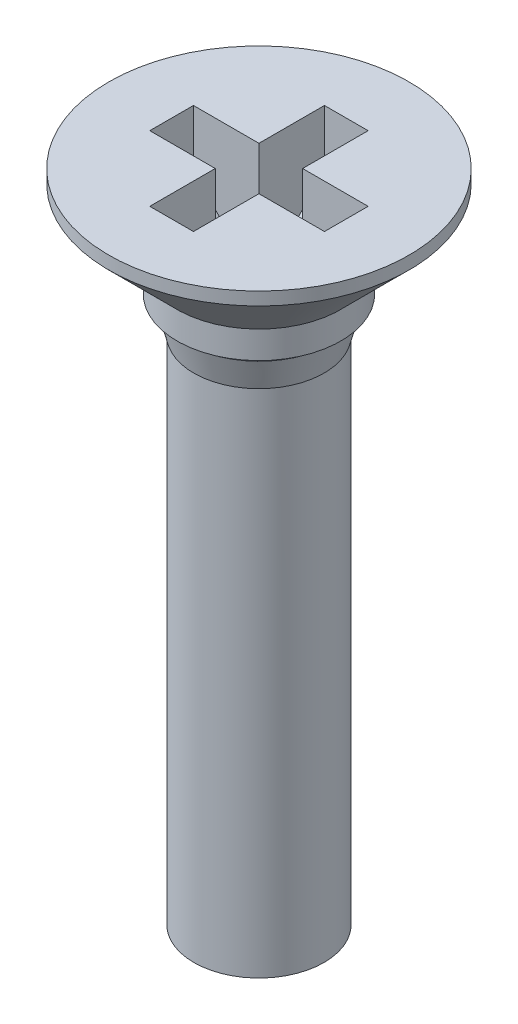
SolidWorks part; units mm, degrees
ref_plane "Vorderseite" through (0, 0, 0) normal (0, 0, 1) x (1, 0, 0)
ref_plane "Oben" through (0, 0, 0) normal (0, 1, 0) x (1, 0, 0)
ref_plane "Rechts" through (0, 0, 0) normal (1, 0, 0) x (0, 0, -1)
sketch "Skizze1" plane through (0, 0, 0) normal (0, 0, 1) x (1, 0, 0)
  line L0 (0, 0) -> (2.75, 0)
  line L1 (2.75, 0) -> (2.75, -0.2375)
  line L2 (2.75, -0.2375) -> (1.5, -1.4875)
  line L3 (1.3375, -1.9875) -> (1.3375, -2.1126)
  line L4 (1.3375, -2.1126) -> (1.1935, -2.65)
  line L5 (1.1935, -2.65) -> (1.1935, -8)
  line L6 (1.1935, -8) -> (0, -8)
  line L7 (0, 0) -> (0, -8) construction
  line L8 (0, 0) -> (0, -8)
  line L10 (1.5, -1.4875) -> (1.5, -1.9875)
  line L12 (1.5, -1.9875) -> (1.3375, -1.9875)
  point P3 (1.3375, -1.65)
  dimension "D1" = 45
  dimension "D2" = 15
  dimension "K" = 1.65
  dimension "DA" = 5.5
  dimension "DK" = 2.387
  dimension "L" = 8
  dimension "DG" = 3
  dimension "A" = 1
  dimension "DF" = 2.675
  dimension "P" = 0.5
revolve "Basis-Rotation" add sketch "Skizze1" angle 360 about L7
sketch "Skizze2" plane through (0, 0, 0) normal (0, 0, 1) x (1, 0, 0)
  line L0 (0, -2.1) -> (0, 0) construction
  line L1 (0, 0) -> (0, -8) construction
  line L2 (-0.55, -2.1) -> (0.55, -2.1)
  line L3 (1.6, 0) -> (1.6, -1.05)
  line L4 (1.6, -1.05) -> (0.55, -2.1)
  line L5 (1.6, 0) -> (-1.6, 0)
  line L6 (-1.6, -1.05) -> (-0.55, -2.1)
  line L7 (-1.6, 0) -> (-1.6, -1.05)
  line L8 (0, -1.05) -> (1.6, -1.05) construction
  line L9 (2.75, 0) -> (-2.75, 0) construction
  line L11 (1.5, -1.4875) -> (2.75, -0.2375) construction
  point P11 (0, 0)
  dimension "M" = 3.2
  dimension "T" = 2.1
extrude "Kreuzschlitz1 H" cut sketch "Skizze2" against normal blind 0.4 and the other way blind 0.4
sketch "Skizze3" plane through (0, 0, 0) normal (1, 0, 0) x (0, 0, -1)
  line L0 (0, -2.1) -> (0, 0) construction
  line L2 (-0.55, -2.1) -> (0.55, -2.1)
  line L3 (1.6, 0) -> (1.6, -1.05)
  line L4 (1.6, -1.05) -> (0.55, -2.1)
  line L5 (1.6, 0) -> (-1.6, 0)
  line L6 (-1.6, -1.05) -> (-0.55, -2.1)
  line L7 (-1.6, 0) -> (-1.6, -1.05)
  line L8 (0, -1.05) -> (1.6, -1.05) construction
  point P11 (0, 0)
extrude "Kreuzschlitz2 H" cut sketch "Skizze3" against normal blind 0.4 and the other way blind 0.4
sketch "Skizze4" plane through (2.4522, 0, -1.8507) normal (0, 1, 0) x (-1, 0, 0)
  line L0 (7.3522, 1.8507) -> (-2.4478, 1.8507) construction
  line L1 (2.4522, -3.0493) -> (2.4522, 6.7507) construction
  line L2 (-2.4478, 1.0342) -> (-2.4478, 2.6672)
  line L3 (-2.4478, 1.0342) -> (0.0059, 1.0342)
  line L4 (0.0059, 1.0342) -> (0.8191, 0.6258)
  line L5 (1.2273, 0.2176) -> (-1.0126, -1.6141)
  line L6 (0.8191, 0.6258) -> (-1.0126, -1.6141)
  line L7 (1.6357, -0.5956) -> (1.2273, 0.2176)
  line L8 (1.6357, -3.0493) -> (1.6357, -0.5956)
  line L9 (1.6357, -3.0493) -> (3.2687, -3.0493)
  line L10 (3.2687, -3.0493) -> (3.2687, -0.5956)
  line L11 (3.2687, -0.5956) -> (3.6772, 0.2176)
  line L12 (2.4522, 1.8507) -> (-1.0126, -1.6141) construction
  line L13 (4.0854, 0.6258) -> (5.917, -1.6141)
  line L14 (3.6772, 0.2176) -> (5.917, -1.6141)
  line L15 (4.8986, 1.0342) -> (4.0854, 0.6258)
  line L16 (7.3522, 1.0342) -> (4.8986, 1.0342)
  line L17 (7.3522, 1.0342) -> (7.3522, 2.6672)
  line L18 (7.3522, 2.6672) -> (4.8986, 2.6672)
  line L19 (4.8986, 2.6672) -> (4.0854, 3.0757)
  line L20 (3.6772, 3.4839) -> (5.917, 5.3156)
  line L21 (4.0854, 3.0757) -> (5.917, 5.3156)
  line L22 (3.2687, 4.2971) -> (3.6772, 3.4839)
  line L23 (3.2687, 6.7507) -> (3.2687, 4.2971)
  line L24 (1.6357, 6.7507) -> (3.2687, 6.7507)
  line L25 (1.6357, 6.7507) -> (1.6357, 4.2971)
  line L26 (1.6357, 4.2971) -> (1.2273, 3.4839)
  line L27 (0.8191, 3.0757) -> (-1.0126, 5.3156)
  line L28 (1.2273, 3.4839) -> (-1.0126, 5.3156)
  line L29 (0.0059, 2.6672) -> (0.8191, 3.0757)
  line L30 (-2.4478, 2.6672) -> (0.0059, 2.6672)
  circle A0 centre (2.4522, 1.8507) radius 4.9 construction
  circle A1 centre (2.4522, 1.8507) radius 2.0415 construction
  circle A2 centre (2.4522, 1.8507) radius 2.579 construction
  dimension "X2" = 4.083
  dimension "X1" = 5.158
  dimension "M" = 9.8
  dimension "D3" = 5.725
  dimension "X3" = 1.633
sketch "Sketch1" plane through (0, -8, 0) normal (0, -1, 0) x (1, 0, 0)
  circle A0 centre (0, 0) radius 1.1935
extrude "Boss-Extrude1" add sketch "Sketch1" along normal blind 4
